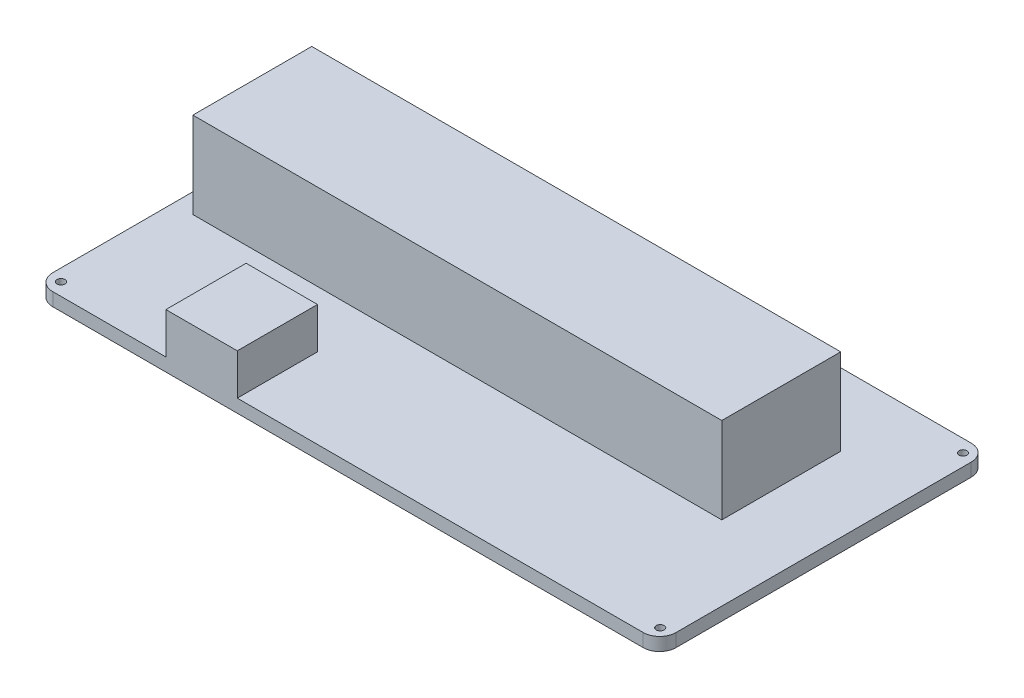
SolidWorks part; units mm, degrees
ref_plane "Plan de face" through (0, 0, 0) normal (0, 0, 1) x (1, 0, 0)
ref_plane "Plan de dessus" through (0, 0, 0) normal (0, 1, 0) x (1, 0, 0)
ref_plane "Plan de droite" through (0, 0, 0) normal (1, 0, 0) x (0, 0, -1)
sketch "Esquisse1" plane through (0, 0, 0) normal (0, 1, 0) x (1, 0, 0)
  line L1 (-38, 20) -> (38, 20)
  line L2 (-38, 20) -> (-38, -20)
  line L3 (-38, -20) -> (38, -20)
  line L4 (38, 20) -> (38, -20)
  line L5 (-38, 20) -> (38, -20) construction
  line L6 (-38, -20) -> (38, 20) construction
  point P0 (0, 0)
  dimension "D1" = 76
  dimension "D2" = 40
extrude "Boss.-Extru.1" add sketch "Esquisse1" along normal blind 1.6
fillet "Congé1" radius 2 4 edges at (38, 0.8, -20) (38, 0.8, 20) (-38, 0.8, -20) (-38, 0.8, 20)
sketch "Esquisse2" plane through (0, 1.6, 0) normal (0, 1, 0) x (1, 0, 0)
  circle A0 centre (-36.5339, -18.4594) radius 0.4797
extrude "Enlèv. mat.-Extru.1" cut sketch "Esquisse2" against normal blind 1.6
mirror "Symétrie1" about plane through (0, 0, 0) normal (1, 0, 0) of "Enlèv. mat.-Extru.1" second plane through (0, 0, 0) second plane normal (0, 0, 1)
sketch "Esquisse3" plane through (0, 1.6, 0) normal (0, 1, 0) x (1, 0, 0)
  line L0 (-38, 0) -> (-35.6, 0) construction
  line L1 (-38, 18) -> (-38, -18) construction
  line L2 (-35.6, 0) -> (-35.6, 50000) construction
  line L3 (-35.6, 19.9798) -> (-35.6, 11.1147) construction
  line L4 (-35.6, 19.9798) -> (-35.6, 11.1829) construction
  line L5 (-35.6, 11.1829) -> (-35.6, 19.9798) construction
  line L6 (-35.6, 11.1829) -> (-35.6, -3.3171)
  line L7 (-35.6, 11.1829) -> (28.9, 11.1829)
  line L8 (-35.6, -3.3171) -> (28.9, -3.3171)
  line L9 (28.9, 11.1829) -> (28.9, -3.3171)
  dimension "D1" = 2.4
  dimension "D2" = 14.5
  dimension "D3" = 64.5
extrude "Boss.-Extru.2" add sketch "Esquisse3" along normal blind 10.5 and the other way blind 3 contours L6 L7 L9 L8
sketch "Esquisse4" plane through (0, 1.6, 0) normal (0, 1, 0) x (1, 0, 0)
  line L0 (-38, -10.2152) -> (-13.5, -10.2152) construction
  line L1 (-38, 18) -> (-38, -18) construction
  line L2 (-36, -20) -> (36, -20) construction
  line L3 (-13.5, -10.2152) -> (-22.2075, -10.2152)
  line L4 (-13.5, -10.2152) -> (-13.5, -20)
  line L5 (-13.5, -20) -> (-22.2075, -20)
  line L6 (-22.2075, -10.2152) -> (-22.2075, -20)
  dimension "D1" = 24.5
extrude "Boss.-Extru.3" add sketch "Esquisse4" along normal blind 5
